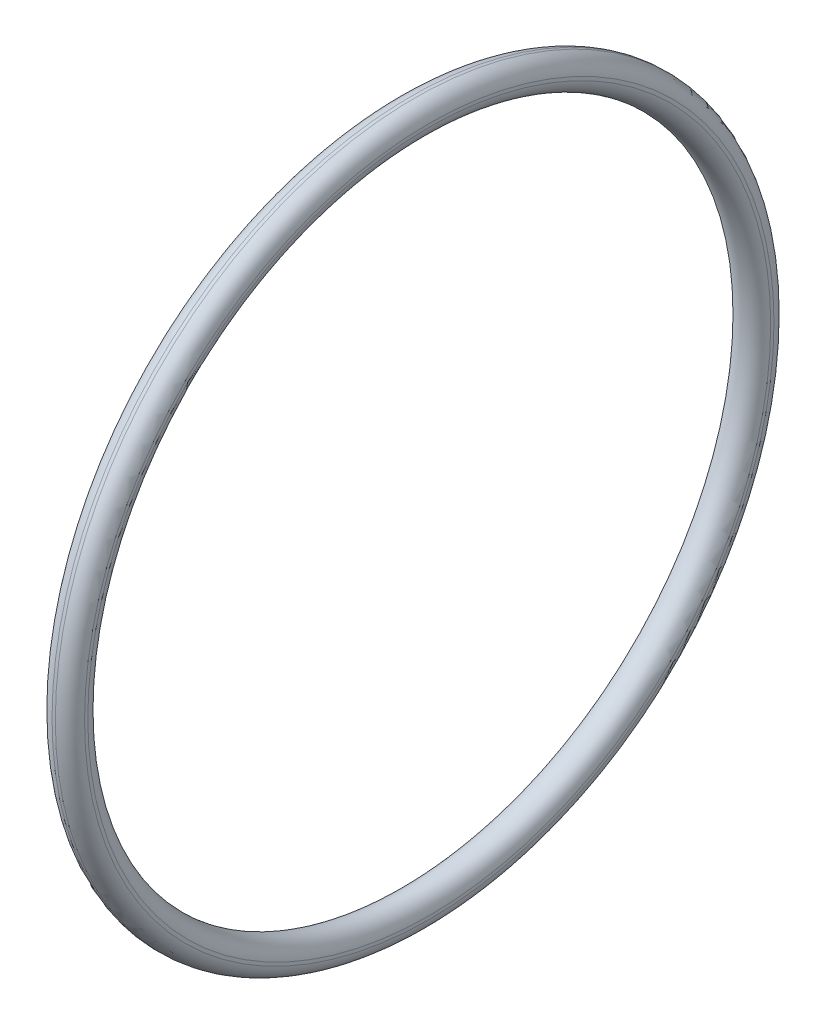
SolidWorks part; units mm, degrees
material "72NBR872 (2)"
ref_plane "Vorne" through (0, 0, 0) normal (0, 0, 1) x (1, 0, 0)
ref_plane "Oben" through (0, 0, 0) normal (0, 1, 0) x (1, 0, 0)
ref_plane "Rechts" through (0, 0, 0) normal (1, 0, 0) x (0, 0, -1)
sketch "Skizze1" plane through (0, 0, 0) normal (0, 0, 1) x (1, 0, 0)
  line L0 (0, 0) -> (14.8056, 0) construction
  line L1 (-0.2, 43.99) -> (0.2, 43.99)
  line L2 (1.99, 41.8) -> (1.99, 42.2)
  arc A0 (-0.2, 43.99) -> (1.99, 41.8) centre (0, 42) ccw
  arc A1 (1.99, 42.2) -> (0.2, 43.99) centre (0, 42) ccw
  dimension "D1" = 4
  dimension "D2" = 80
  dimension "D3" = 0.4
revolve "Rotation1" add sketch "Skizze1" angle 360 about L0
